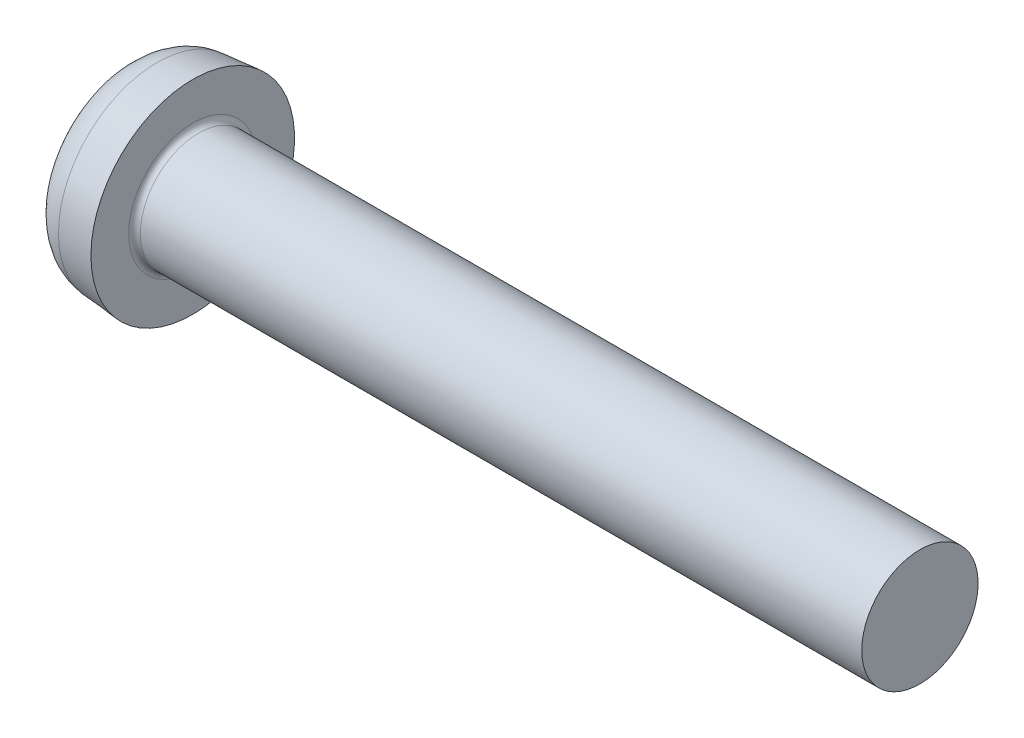
SolidWorks part; units mm, degrees
material "Alloy Steel"
ref_plane "Front Plane" through (0, 0, 0) normal (0, 0, 1) x (1, 0, 0)
ref_plane "Top Plane" through (0, 0, 0) normal (0, 1, 0) x (1, 0, 0)
ref_plane "Right Plane" through (0, 0, 0) normal (1, 0, 0) x (0, 0, -1)
sketch "BodySke" plane through (0, 0, 0) normal (0, 0, 1) x (1, 0, 0)
  line L0 (0, 0) -> (111.3824, 0) construction
  line L1 (0, 0) -> (0, 8) construction
  line L2 (5.4, 4) -> (5.4, 7)
  line L3 (5.4, 7) -> (2.9561, 6.7862)
  line L4 (5.4, 4) -> (55.4, 4)
  line L5 (55.4, 4) -> (55.4, 0)
  line L7 (0, 0) -> (55.4, 0)
  arc A0 (2.9561, 6.7862) -> (0.6811, 4.9045) centre (3.1827, 4.1961) ccw
  arc A1 (0.6811, 4.9045) -> (0, 0) centre (18, 0) ccw
  point P10 (55.4, 3.445)
  dimension "Thread_minor" = 6.89
  dimension "Head_side_radius" = 2.6
  dimension "Head_radius" = 18
  dimension "Diameter" = 8
  dimension "Head_height" = 5.4
  dimension "Length" = 50
  dimension "D1" = 5
  dimension "Head_dia" = 14
revolve "BaseBody" add sketch "BodySke" angle 360 about L0
cosmetic thread "ThreadCosmetic" [suppressed] parameters "Thread_minor"=6.89
fillet "Fillet1" radius 0.4 1 edges at (5.4, 0, 4)
ref_plane "Plane1" through (4.36, 0, 0) normal (1, 0, 0) x (0, 0, -1)
sketch "RecSkeTop" plane through (0, 0, 0) normal (1, 0, 0) x (0, 0, -1)
  line L1 (-1.155, 5.25) -> (1.155, 5.25)
  line L2 (-1.155, 5.25) -> (-1.155, -5.25)
  line L3 (-1.155, -5.25) -> (1.155, -5.25)
  line L4 (1.155, 5.25) -> (1.155, -5.25)
  point P4 (-1.155, 0)
  point P7 (0, 0)
  point P9 (0, 5.25)
  dimension "Cross_dia" = 10.5
  dimension "D2" = 2.31
sketch "RecSkeBot" plane through (4.36, 0, 0) normal (1, 0, 0) x (0, 0, -1)
  line L0 (-1.155, 5.25) -> (-1.155, -5.25) construction
  line L1 (-1.155, 3.0762) -> (1.155, 3.0762)
  line L2 (-1.155, 3.0762) -> (-1.155, -3.0762)
  line L3 (-1.155, -3.0762) -> (1.155, -3.0762)
  line L4 (1.155, 3.0762) -> (1.155, -3.0762)
  line L5 (1.155, 5.25) -> (1.155, -5.25) construction
  dimension "D1" = 6.1524
  dimension "D2" = 3.0762
loft "Recess" cut profiles "RecSkeTop", "RecSkeBot"
pattern_circular "RecPat" count 2 every 90 about axis through (0, 0, 0) along (1, 0, 0) of "Recess"
sketch "RecCorSke" plane through (0, 0, 0) normal (0, 0, 1) x (1, 0, 0)
  line L0 (0, 0) -> (57.5987, 0) construction
  line L1 (0, 0) -> (0, 2.541)
  line L3 (0, 2.541) -> (4.36, 2.2361)
  line L4 (4.36, 2.2361) -> (5.0866, 0)
  line L5 (5.0866, 0) -> (0, 0)
  dimension "D1" = 18
  dimension "D2" = 4.36
  dimension "D3" = 2.541
  dimension "D4" = 4
revolve "RecessCore" cut sketch "RecCorSke" angle 360 about L0
equation "\"Thread_minor@ThreadCosmetic\"=\"Thread_minor@BodySke\""
equation "\"D2@RecSkeTop\" = \"Cross_dia@RecSkeTop\" * 0.22"
equation "\"D1@RecSkeBot\" = \"Cross_dia@RecSkeTop\" - 2 * \"Cross_depth@Plane1\" *  tan( 26.5 * 0.017453292 ) "
equation "\"D2@RecSkeBot\" = \"D1@RecSkeBot\" / 2"
equation "\"D2@RecCorSke\" = \"Cross_depth@Plane1\""
equation "\"D3@RecCorSke\" = \"D2@RecSkeTop\" * 1.1"
equation "\"Mass\"= \"SW-질량\" / 1000"
equation "\"Head_side_radius@BodySke\"= \"Head_height@BodySke\" * ( 2.6 / 5.4 )"
equation "\"Head_radius@BodySke\"= \"Head_height@BodySke\" * ( 18 / 5.4 )"
equation "\"Thread_minor@BodySke\"= \"Diameter@BodySke\" * ( 6.89 / 8 )"
equation "\"Cross_dia@RecSkeTop\"= \"Head_dia@BodySke\" * ( 6 / 8 )"
equation "\"Cross_depth@Plane1\"= \"Head_height@BodySke\" * ( 4.36 / 5.4 )"
